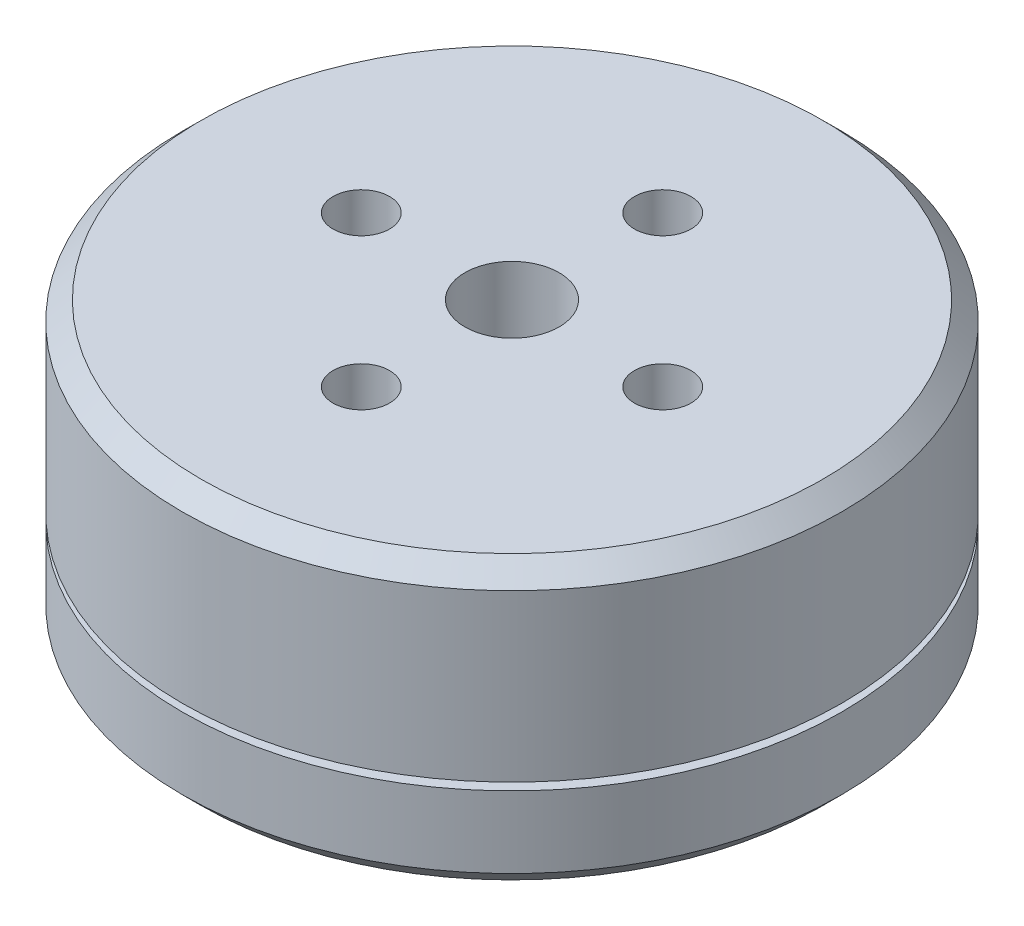
SolidWorks part; units mm, degrees
ref_plane "Front Plane" through (0, 0, 0) normal (0, 0, 1) x (1, 0, 0)
ref_plane "Top Plane" through (0, 0, 0) normal (0, 1, 0) x (1, 0, 0)
ref_plane "Right Plane" through (0, 0, 0) normal (1, 0, 0) x (0, 0, -1)
sketch "Sketch1" plane through (0, 0, 0) normal (0, 1, 0) x (1, 0, 0)
  circle A0 centre (0, 0) radius 17.5
  dimension "D1" = 35
extrude "Boss-Extrude1" add sketch "Sketch1" along normal blind 15
sketch "Sketch2" plane through (0, 15, 0) normal (0, 1, 0) x (1, 0, 0)
  line L0 (-8, 0) -> (8, 0) construction
  line L1 (0, 8) -> (0, -8) construction
  circle A0 centre (-8, 0) radius 1.5
  circle A1 centre (8, 0) radius 1.5
  circle A2 centre (0, 8) radius 1.5
  circle A3 centre (0, -8) radius 1.5
  point P8 (0, 0)
  point P9 (0, 0)
  dimension "D2" = 3
  dimension "D1" = 16
extrude "Cut-Extrude1" cut sketch "Sketch2" against normal blind 3
sketch "Sketch3" plane through (0, 0, 0) normal (0, -1, 0) x (1, 0, 0)
  line L0 (-8, 0) -> (8, 0) construction
  line L1 (0, 9.5) -> (0, -9.5) construction
  circle A0 centre (0, 9.5) radius 1.5
  circle A1 centre (0, -9.5) radius 1.5
  circle A2 centre (8, 0) radius 1.5
  circle A3 centre (-8, 0) radius 1.5
  point P8 (0, 0)
  point P9 (0, 0)
  dimension "D3" = 3
  dimension "D1" = 19
  dimension "D2" = 16
extrude "Cut-Extrude2" cut sketch "Sketch3" against normal blind 3
ref_plane "Plane1" through (0, 5, 0) normal (0, -1, 0) x (-1, 0, 0)
sketch "Sketch4" plane through (0, 5, 0) normal (0, -1, 0) x (-1, 0, 0)
  circle A0 centre (0, 0) radius 17.5 construction
  circle A1 centre (0, 0) radius 17.5
  circle A2 centre (0, 0) radius 16.5
  dimension "D1" = 1
extrude "Cut-Extrude3" cut sketch "Sketch4" against normal blind 0.2 and the other way blind 0.2
chamfer "Chamfer1" distance 1 angle 45 2 edges at (0, 0, 17.5) (0, 15, 17.5)
sketch "Sketch5" plane through (0, 15, 0) normal (0, 1, 0) x (1, 0, 0)
  circle A0 centre (0, 0) radius 2.5
  dimension "D1" = 5
extrude "Cut-Extrude4" cut sketch "Sketch5" against normal through all
